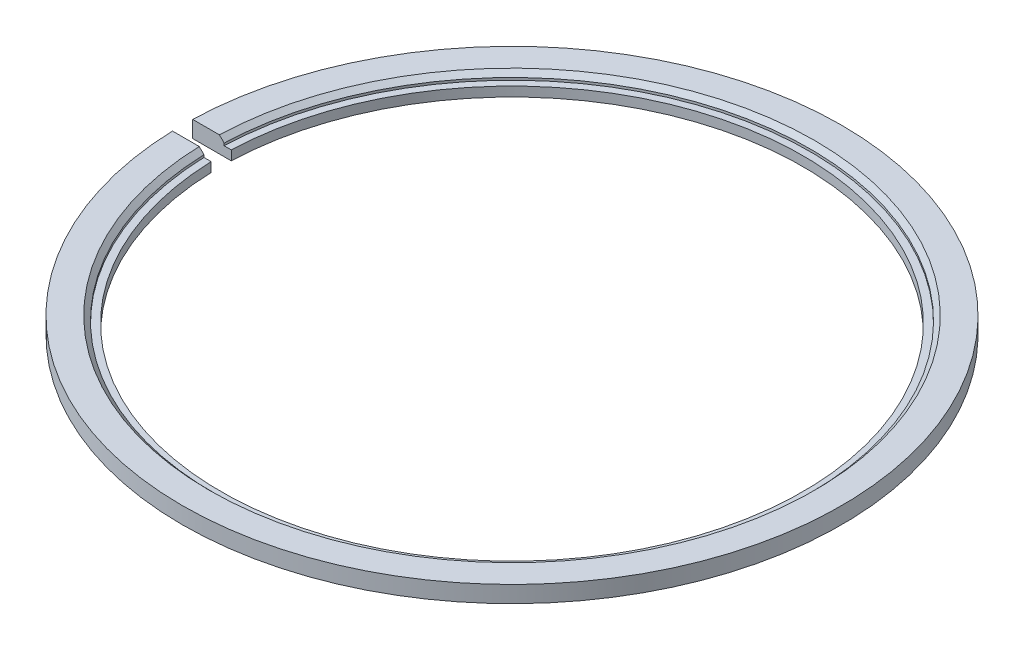
SolidWorks part; units mm, degrees
material "AISI 1045 Steel, cold drawn"
ref_plane "Front Plane" through (0, 0, 0) normal (0, 0, 1) x (1, 0, 0)
ref_plane "Top Plane" through (0, 0, 0) normal (0, 1, 0) x (1, 0, 0)
ref_plane "Right Plane" through (0, 0, 0) normal (1, 0, 0) x (0, 0, -1)
sketch "Sketch1" plane through (0, 0, 0) normal (0, 0, 1) x (1, 0, 0)
  line L0 (0, 0) -> (0, 3.6946) construction
  line L14 (35.2425, 1.778) -> (31.877, 1.778)
  line L16 (31.877, 1.778) -> (31.877, 1.016)
  line L17 (31.877, 1.016) -> (31.115, 1.016)
  line L18 (31.115, 1.016) -> (31.115, 0)
  line L19 (31.115, 0) -> (35.2425, 0)
  line L20 (35.2425, 0) -> (35.2425, 1.778)
  dimension "D1" = 62.23
  dimension "D2" = 0.762
  dimension "D3" = 70.485
  dimension "D4" = 1.016
  dimension "D5" = 1.778
other "AlignGroup1"
revolve "Revolve1" add sketch "Sketch1" angle 360 about L0
chamfer "Chamfer1" distance 0.508 angle 45 1 edges at (0, 1.778, -31.877)
sketch "Sketch4" plane through (0, 1.778, 0) normal (0, 1, 0) x (1, 0, 0)
  line L7 (-35.2425, -1.0795) -> (-31.0963, -1.0795)
  line L8 (-35.2425, -1.0795) -> (-35.2425, 1.0795)
  line L9 (-35.2425, 1.0795) -> (-31.0963, 1.0795)
  line L10 (-31.0963, -1.0795) -> (-31.0963, 1.0795)
  line L11 (-33.1694, 1.0795) -> (-33.1694, -1.0795) construction
  line L12 (-35.2425, 0) -> (-31.0963, 0) construction
  circle A4 centre (0, 0) radius 31.115 construction
  circle A6 centre (0, 0) radius 35.2425 construction
  point P5 (-33.1694, 0)
  dimension "D1" = 2.159
extrude "Cut-Extrude1" cut sketch "Sketch4" against normal through all
